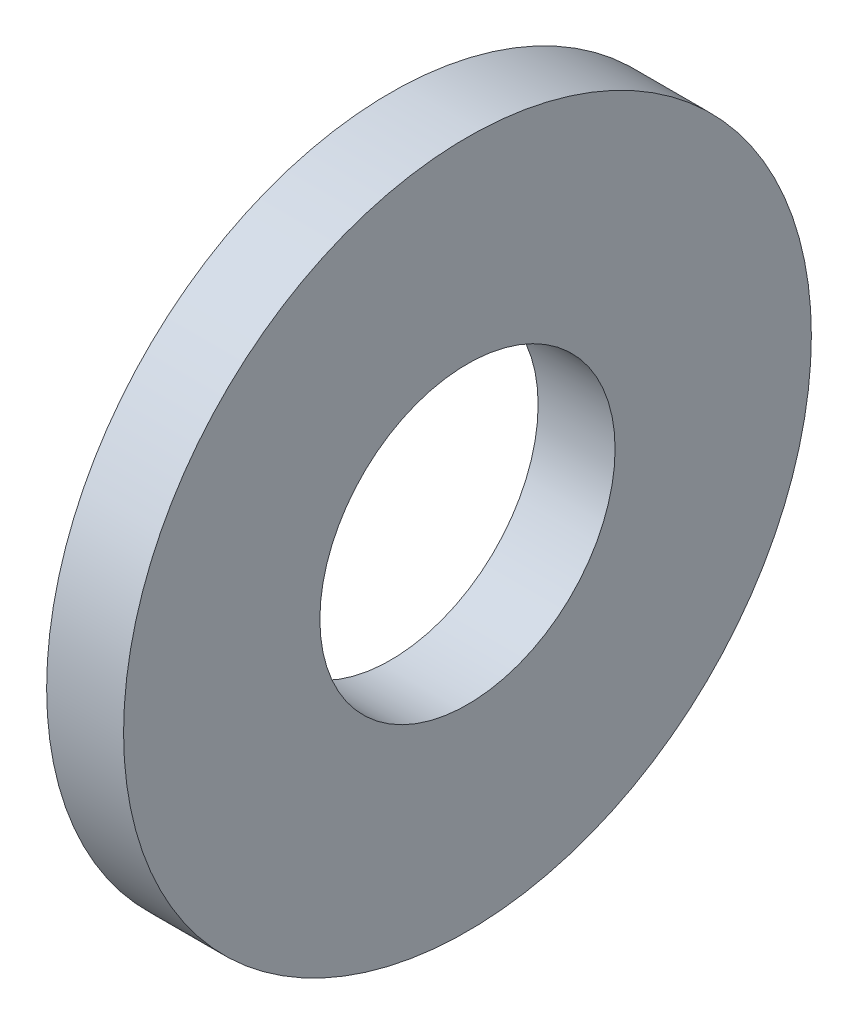
SolidWorks part; units mm, degrees
ref_plane "Plane1"
ref_plane "Plane2" through (0, 0, 0) normal (0, 1, 0) x (1, 0, 0)
ref_plane "Plane3" through (0, 0, 0) normal (1, 0, 0) x (0, 0, -1)
sketch "Sketch1" plane through (0, 0, 0) normal (0, 0, 1) x (1, 0, 0)
  line L0 (-34.925, 0) -> (9.525, 0) construction
  line L1 (0, 2.3876) -> (0, 5.5626)
  line L2 (0, 5.5626) -> (-1.2446, 5.5626)
  line L3 (-1.2446, 5.5626) -> (-1.2446, 2.3876)
  line L4 (-1.2446, 2.3876) -> (0, 2.3876)
  dimension "Thickness" = 1.2446
  dimension "Inside_dia" = 4.7752
  dimension "Outside_dia" = 11.1252
revolve "Base-Revolve" add sketch "Sketch1" angle 360 about L0
